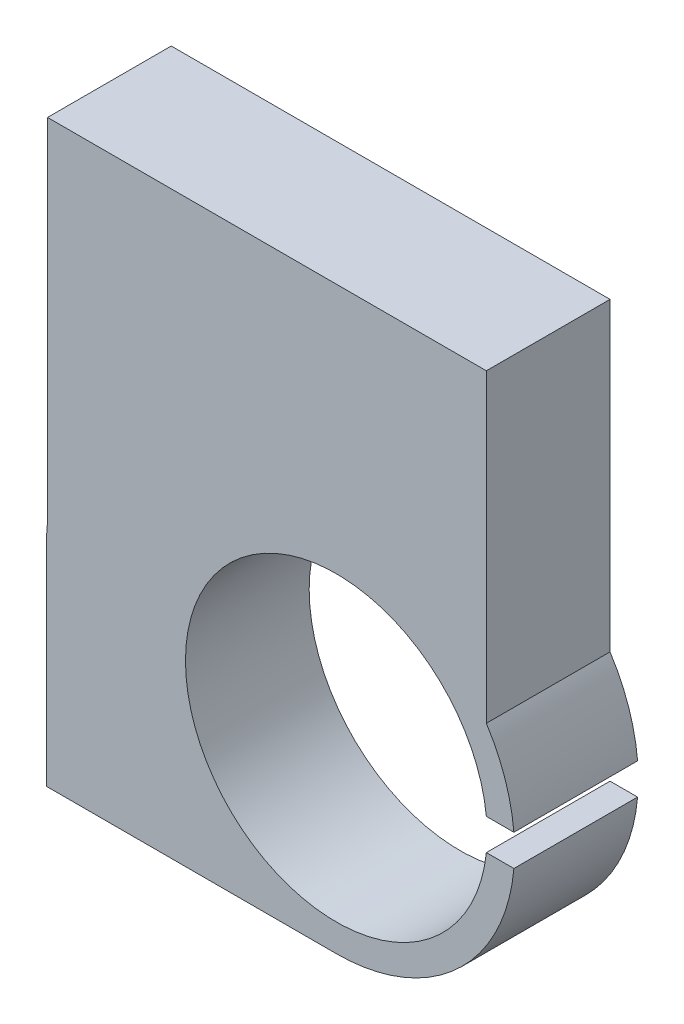
SolidWorks part; units mm, degrees
ref_plane "Front Plane" through (0, 0, 0) normal (0, 0, 1) x (1, 0, 0)
ref_plane "Top Plane" through (0, 0, 0) normal (0, 1, 0) x (1, 0, 0)
ref_plane "Right Plane" through (0, 0, 0) normal (1, 0, 0) x (0, 0, -1)
sketch "Sketch7" plane through (0, 0, 0) normal (0, 0, 1) x (1, 0, 0)
  line L0 (-29.0092, -3.5603) -> (114.9908, -3.5603)
  line L1 (-10.5822, 1.4397) -> (96.5637, 1.4397)
  line L8 (126.3217, 6.8147) -> (124.5637, 6.8147)
  line L9 (126.3217, 8.8147) -> (124.5637, 8.8147)
  line L10 (42.9908, -3.5603) -> (42.9908, 54.826) construction
  line L11 (-40.3402, 8.8147) -> (-38.5822, 8.8147)
  line L12 (-40.3402, 6.8147) -> (-38.5822, 6.8147)
  line L19 (-38.5822, 13.9588) -> (-38.5822, 33.4397)
  line L20 (-38.5822, 33.4397) -> (-10.5822, 33.4397)
  line L21 (-10.5822, 33.4397) -> (-10.5822, 1.4397)
  line L22 (96.5637, 33.4397) -> (96.5637, 1.4397)
  line L23 (124.5637, 13.9588) -> (124.5637, 33.4397)
  line L24 (124.5637, 33.4397) -> (96.5637, 33.4397)
  arc A0 (124.5637, 8.8147) -> (124.5637, 6.8147) centre (114.9908, 7.8147) ccw
  arc A1 (-38.5822, 6.8147) -> (-38.5822, 8.8147) centre (-29.0092, 7.8147) ccw
  arc A2 (114.9908, -3.5603) -> (126.3217, 6.8147) centre (114.9908, 7.8147) ccw
  arc A3 (-38.5822, 13.9588) -> (-40.3402, 8.8147) centre (-29.0092, 7.8147) ccw
  arc A4 (-40.3402, 6.8147) -> (-29.0092, -3.5603) centre (-29.0092, 7.8147) ccw
  arc A5 (126.3217, 8.8147) -> (124.5637, 13.9588) centre (114.9908, 7.8147) ccw
  dimension "D2" = 19.25
  dimension "D3" = 1.75
  dimension "D11" = 28
  dimension "D5" = 2
  dimension "D1" = 144
  dimension "D4" = 5
  dimension "D6" = 1
  dimension "D12" = 32
extrude "Boss-Extrude3" add sketch "Sketch7" along normal blind 28
fillet "Fillet1" radius 10 2 edges at (96.5637, 1.4397, 14) (-10.5822, 1.4397, 14)
sketch "Sketch8" plane through (0, 1.4397, 0) normal (0, 1, 0) x (1, 0, 0)
  line L0 (42.9908, 0) -> (42.9908, -28) construction
  line L1 (86.5637, 0) -> (-0.5822, 0) construction
  line L2 (86.5637, -28) -> (-0.5822, -28) construction
  line L3 (86.5637, -14) -> (-0.5822, -14) construction
  line L4 (38.9908, -11.5) -> (46.9908, -11.5)
  line L5 (38.9908, -11.5) -> (38.9908, -16.5)
  line L6 (38.9908, -16.5) -> (46.9908, -16.5)
  line L7 (46.9908, -11.5) -> (46.9908, -16.5)
  line L8 (86.5637, -28) -> (86.5637, 0) construction
  line L9 (-0.5822, 0) -> (-0.5822, -28) construction
  circle A0 centre (63.9908, -14) radius 9.5
  circle A1 centre (21.9908, -14) radius 9.5
  dimension "D5" = 19
  dimension "D7" = 21
  dimension "D1" = 5
  dimension "D2" = 8
  dimension "D3" = 4
  dimension "D4" = 2.5
  dimension "D6" = 21
extrude "Cut-Extrude4" cut sketch "Sketch8" against normal up to surface (5 mm away) up to face at (42.9908, -3.5603, 14)
sketch "Sketch10" plane through (0, 33.4397, 0) normal (0, 1, 0) x (1, 0, 0)
  line L0 (124.5637, -14) -> (-38.5822, -14) construction
  line L1 (124.5637, -28) -> (124.5637, 0) construction
  line L2 (-38.5822, -28) -> (-38.5822, 0) construction
  line L3 (110.4908, 0) -> (110.4908, -28) construction
  line L4 (124.5637, 0) -> (96.5637, 0) construction
  line L5 (124.5637, -28) -> (96.5637, -28) construction
  line L6 (-24.5092, 0) -> (-24.5092, -28) construction
  line L7 (-10.5822, 0) -> (-38.5822, 0) construction
  line L8 (-10.5822, -28) -> (-38.5822, -28) construction
  line L9 (86.5637, 0) -> (-0.5822, 0) construction
  circle A0 centre (110.4908, -14) radius 1.75
  circle A1 centre (-24.5092, -14) radius 1.75
  point P30 (42.9908, 0)
  dimension "D1" = 3.5
  dimension "D2" = 135
  dimension "D3" = 67.5
extrude "Cut-Extrude6" cut sketch "Sketch10" against normal blind 10
sketch "Sketch13" plane through (0, 33.4397, 0) normal (0, 1, 0) x (1, 0, 0)
  line L0 (124.5637, -28) -> (96.5637, -28) construction
  line L1 (108.6144, -17.25) -> (112.3671, -17.25)
  line L2 (112.3671, -17.25) -> (114.2435, -14)
  line L3 (114.2435, -14) -> (112.3671, -10.75)
  line L4 (112.3671, -10.75) -> (108.6144, -10.75)
  line L5 (108.6144, -10.75) -> (106.738, -14)
  line L6 (106.738, -14) -> (108.6144, -17.25)
  line L7 (-20.7565, -14) -> (-22.6329, -10.75)
  line L8 (-22.6329, -10.75) -> (-26.3856, -10.75)
  line L9 (-26.3856, -10.75) -> (-28.262, -14)
  line L10 (-28.262, -14) -> (-26.3856, -17.25)
  line L11 (-26.3856, -17.25) -> (-22.6329, -17.25)
  line L12 (-22.6329, -17.25) -> (-20.7565, -14)
  circle A0 centre (110.4908, -14) radius 3.25 construction
  circle A1 centre (-24.5092, -14) radius 3.25 construction
  dimension "D1" = 6.5
extrude "Cut-Extrude9" cut sketch "Sketch13" against normal blind 5
sketch "Sketch14" [suppressed] plane through (0, 0, 28) normal (0, 0, 1) x (1, 0, 0)
  line L1 (-82.4893, 23.5071) -> (44.7899, 150.7863)
  line L2 (-82.4893, 23.5071) -> (44.7899, -103.7721)
  line L3 (44.7899, -103.7721) -> (172.0692, 23.5071)
  line L4 (44.7899, 150.7863) -> (172.0692, 23.5071)
  line L6 (124.4774, 32.3147) -> (96.4774, 32.3147) construction
  dimension "D1" = 180
  dimension "D2" = 180
  dimension "D3" = 45
sketch "Sketch11" plane through (0, 0, 28) normal (0, 0, 1) x (1, 0, 0)
  line L1 (-81.97, 62.499) -> (96.4919, 62.499)
  line L2 (-81.97, 62.499) -> (-81.97, -13.3564)
  line L3 (-81.97, -13.3564) -> (96.4919, -13.3564)
  line L4 (96.4919, 62.499) -> (96.4919, -13.3564)
extrude "Cut-Extrude7" cut sketch "Sketch11" against normal blind 56
sketch "Sketch15" plane through (96.4919, 0, 0) normal (-1, 0, 0) x (0, 0, 1)
  line L1 (7.8931, 34.5927) -> (32.6535, 34.5927)
  line L2 (7.8931, 34.5927) -> (7.8931, -6.1058)
  line L3 (7.8931, -6.1058) -> (32.6535, -6.1058)
  line L4 (32.6535, 34.5927) -> (32.6535, -6.1058)
extrude "Cut-Extrude10" cut sketch "Sketch15" against normal blind 39
